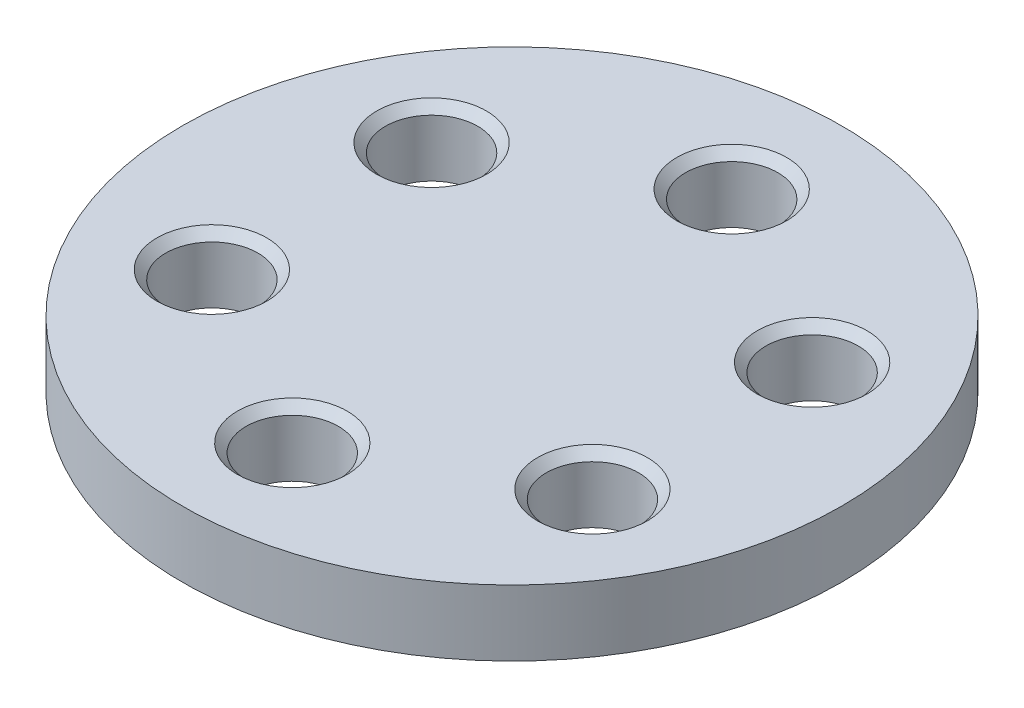
SolidWorks part; units mm, degrees
material "1345 Сплав"
ref_plane "Спереди" through (0, 0, 0) normal (0, 0, 1) x (1, 0, 0)
ref_plane "Сверху" through (0, 0, 0) normal (0, 1, 0) x (1, 0, 0)
ref_plane "Справа" through (0, 0, 0) normal (1, 0, 0) x (0, 0, -1)
other "Configuration Table"
sketch "Эскиз1" plane through (0, 41, 0) normal (0, -1, 0) x (1, 0, 0)
  circle A0 centre (0, 0) radius 15
  dimension "D1" = 30
extrude "Бобышка-Вытянуть1" add sketch "Эскиз1" against normal up to surface (3 mm away)
hole_wizard "Сверло под метчик  спиральное M41" positions "Эскиз2" profile "Эскиз3" hole size "M4x0.7" standard "DIN" end condition through all
sketch "Эскиз2" plane through (0, 44, 0) normal (0, 1, 0) x (1, 0, 0)
  line L0 (0, 0) -> (0, 10) construction
  circle A0 centre (0, 0) radius 10 construction
  point P6 (0, 10)
  point P14 (8.6603, 5)
  point P15 (8.6603, -5)
  point P16 (0, -10)
  point P17 (-8.6603, -5)
  point P18 (-8.6603, 5)
  point P24 (0, 0)
  point P25 (0, 0)
  point P26 (0, 0)
  point P27 (0, 0)
  dimension "D1" = 20
  dimension "D3" = 10
  dimension "D2" = 6
sketch "Эскиз3" plane through (-8.6603, 44, -5) normal (1, 0, 0) x (0, 0, 1)
  line L0 (0, 0) -> (0, 3)
  line L1 (0, 3) -> (2.1, 3)
  line L2 (2.1, 3) -> (2.1, 0.4)
  line L3 (2.1, 0.4) -> (2.5, 0)
  line L5 (2.5, 0) -> (0, 0)
  line L6 (-2.1, 0.4) -> (-2.5, 0) construction
  line L11 (0, -6.35) -> (0, 107.95) construction
  dimension "Диаметр сквозного отверстия" = 4.2
  dimension "Глубина сквозного отверстия" = 3
  dimension "Диаметр передней зенковки" = 5
  dimension "Угол передней зенковки" = 90
